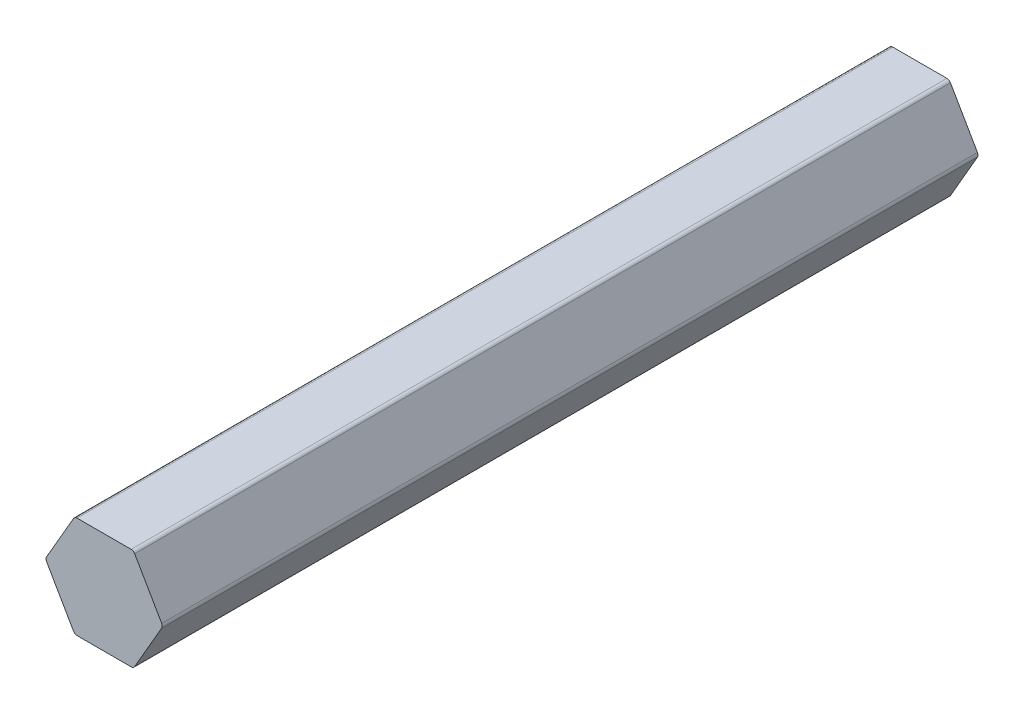
SolidWorks part; units mm, degrees
ref_plane "Front Plane" through (0, 0, 0) normal (0, 0, 1) x (1, 0, 0)
ref_plane "Top Plane" through (0, 0, 0) normal (0, 1, 0) x (1, 0, 0)
ref_plane "Right Plane" through (0, 0, 0) normal (1, 0, 0) x (0, 0, -1)
ref_plane "Plane1" through (0, 0, -228.6) normal (0, 0, -1) x (-1, 0, 0)
sketch "Sketch1" plane through (0, 0, -228.6) normal (0, 0, -1) x (-1, 0, 0)
  line L0 (3.8055, -6.0833) -> (7.171, -0.254)
  line L1 (7.171, 0.254) -> (3.8055, 6.0833)
  line L2 (3.3655, 6.3373) -> (-3.3655, 6.3373)
  line L3 (-3.8055, 6.0833) -> (-7.171, 0.254)
  line L4 (-7.171, -0.254) -> (-3.8055, -6.0833)
  line L5 (-3.3655, -6.3373) -> (3.3655, -6.3373)
  arc A0 (3.3655, -6.3373) -> (3.8055, -6.0833) centre (3.3655, -5.8293) ccw
  arc A1 (7.171, -0.254) -> (7.171, 0.254) centre (6.7311, 0) ccw
  arc A2 (3.8055, 6.0833) -> (3.3655, 6.3373) centre (3.3655, 5.8293) ccw
  arc A3 (-3.3655, 6.3373) -> (-3.8055, 6.0833) centre (-3.3655, 5.8293) ccw
  arc A4 (-7.171, 0.254) -> (-7.171, -0.254) centre (-6.7311, 0) ccw
  arc A5 (-3.8055, -6.0833) -> (-3.3655, -6.3373) centre (-3.3655, -5.8293) ccw
extrude "Boss-Extrude1" add sketch "Sketch1" against normal blind 101.6
